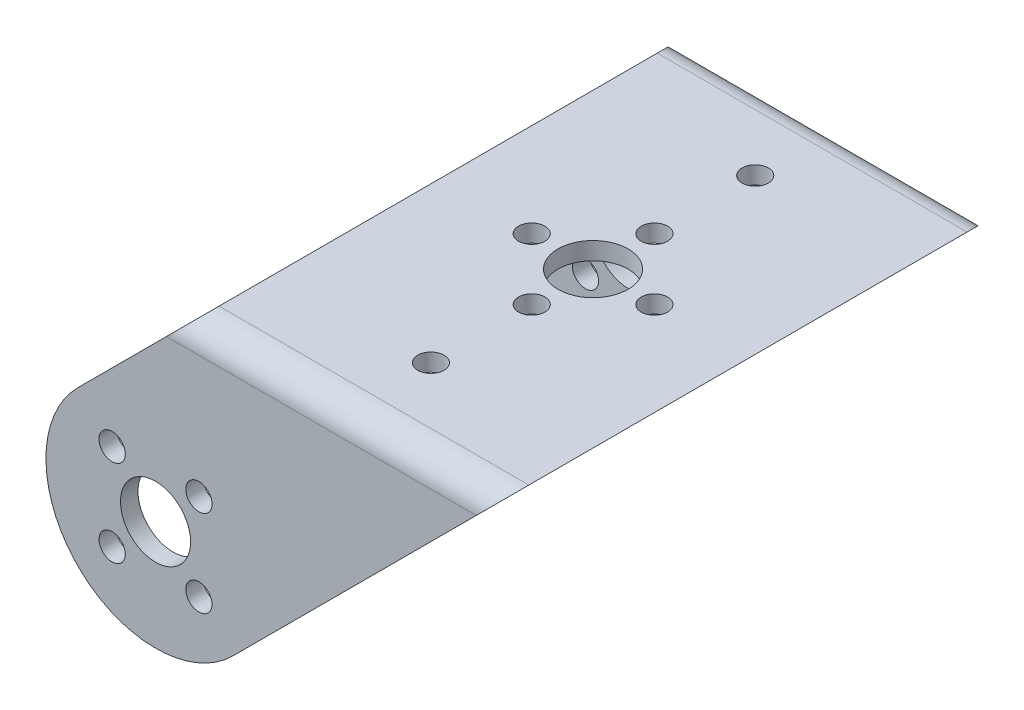
SolidWorks part; units mm, degrees
ref_plane "Front" through (0, 0, 0) normal (0, 0, 1) x (1, 0, 0)
ref_plane "Top" through (0, 0, 0) normal (0, 1, 0) x (1, 0, 0)
ref_plane "Right" through (0, 0, 0) normal (1, 0, 0) x (0, 0, -1)
sketch "草图1" plane through (0, 0, 0) normal (0, 0, 1) x (1, 0, 0)
  line L0 (8.8388, -8.8388) -> (39.598, 21.9203)
  line L1 (-8.8388, 8.8388) -> (4.2426, 21.9203)
  line L2 (39.598, 21.9203) -> (4.2426, 21.9203)
  arc A0 (-8.8388, 8.8388) -> (8.8388, -8.8388) centre (0, 0) ccw
  circle A1 centre (0, 0) radius 4
  circle A8 centre (4.9497, -4.9497) radius 1.5
  circle A9 centre (-4.9497, -4.9497) radius 1.5
  circle A10 centre (-4.9497, 4.9497) radius 1.5
  circle A11 centre (4.9497, 4.9497) radius 1.5
  point P16 (0, 0)
  point P20 (0, 0)
  dimension "D1" = 4
extrude "凸台-拉伸1" add sketch "草图1" along normal blind 2
sketch "草图2" plane through (0, 0, 0) normal (0, 0, -1) x (-1, 0, 0)
  line L0 (-39.598, 21.9203) -> (-4.2426, 21.9203)
  line L1 (-2.2426, 19.9203) -> (-4.2426, 21.9203)
  line L2 (-37.598, 19.9203) -> (-2.2426, 19.9203)
  line L3 (-8.8388, -8.8388) -> (-39.598, 21.9203) construction
  line L4 (-4.2426, 21.9203) -> (8.8388, 8.8388) construction
  line L5 (-39.598, 21.9203) -> (-37.598, 19.9203)
extrude "凸台-拉伸2" add sketch "草图2" along normal blind 52
sketch "草图3" plane through (0, 0, -52) normal (0, 0, -1) x (-1, 0, 0)
  line L0 (-2.2426, 19.9203) -> (-4.2426, 21.9203) construction
  line L1 (-39.598, 21.9203) -> (-37.598, 19.9203) construction
  line L2 (-4.2426, 21.9203) -> (-39.598, 21.9203) construction
  line L3 (-2.2426, 19.9203) -> (8.8388, 8.8388) construction
  line L4 (-8.8388, -8.8388) -> (-37.598, 19.9203) construction
  line L5 (-2.2426, 19.9203) -> (-4.2426, 21.9203)
  line L6 (-39.598, 21.9203) -> (-37.598, 19.9203)
  line L7 (-4.2426, 21.9203) -> (-39.598, 21.9203)
  line L8 (-2.2426, 19.9203) -> (8.8388, 8.8388)
  line L9 (-8.8388, -8.8388) -> (-37.598, 19.9203)
  circle A2 centre (0, 0) radius 4 construction
  arc A5 (-8.8388, -8.8388) -> (8.8388, 8.8388) centre (0, 0) ccw construction
  circle A8 centre (0, 0) radius 4
  arc A11 (-8.8388, -8.8388) -> (8.8388, 8.8388) centre (0, 0) ccw
  circle A12 centre (-4.9497, -4.9497) radius 1.5 construction
  circle A13 centre (-4.9497, 4.9497) radius 1.5 construction
  circle A14 centre (4.9497, 4.9497) radius 1.5 construction
  circle A15 centre (4.9497, -4.9497) radius 1.5 construction
  circle A16 centre (-4.9497, -4.9497) radius 1.5
  circle A17 centre (-4.9497, 4.9497) radius 1.5
  circle A18 centre (4.9497, 4.9497) radius 1.5
  circle A19 centre (4.9497, -4.9497) radius 1.5
extrude "凸台-拉伸3" add sketch "草图3" along normal blind 2
fillet "圆角1" radius 3 2 edges at (21.9203, 21.9203, 2) (21.9203, 21.9203, -54)
fillet "圆角2" radius 1 2 edges at (19.9203, 19.9203, 0) (19.9203, 19.9203, -52)
sketch "草图4" plane through (0, 21.9203, 0) normal (0, 1, 0) x (1, 0, 0)
  circle A0 centre (21.9203, 26) radius 4
  circle A2 centre (14.9203, 26) radius 1.5
  circle A3 centre (21.9203, 33) radius 1.5
  circle A4 centre (28.9203, 26) radius 1.5
  circle A5 centre (21.9203, 19) radius 1.5
  point P18 (21.9203, 26)
  dimension "D1" = 4
extrude "切除-拉伸1" cut sketch "草图4" against normal blind 2
sketch "草图5" plane through (0, 21.9203, 0) normal (0, 1, 0) x (1, 0, 0)
  circle A0 centre (21.9203, 44.5) radius 1.5
  circle A1 centre (21.9203, 7.5) radius 1.5
extrude "切除-拉伸2" cut sketch "草图5" against normal blind 2
